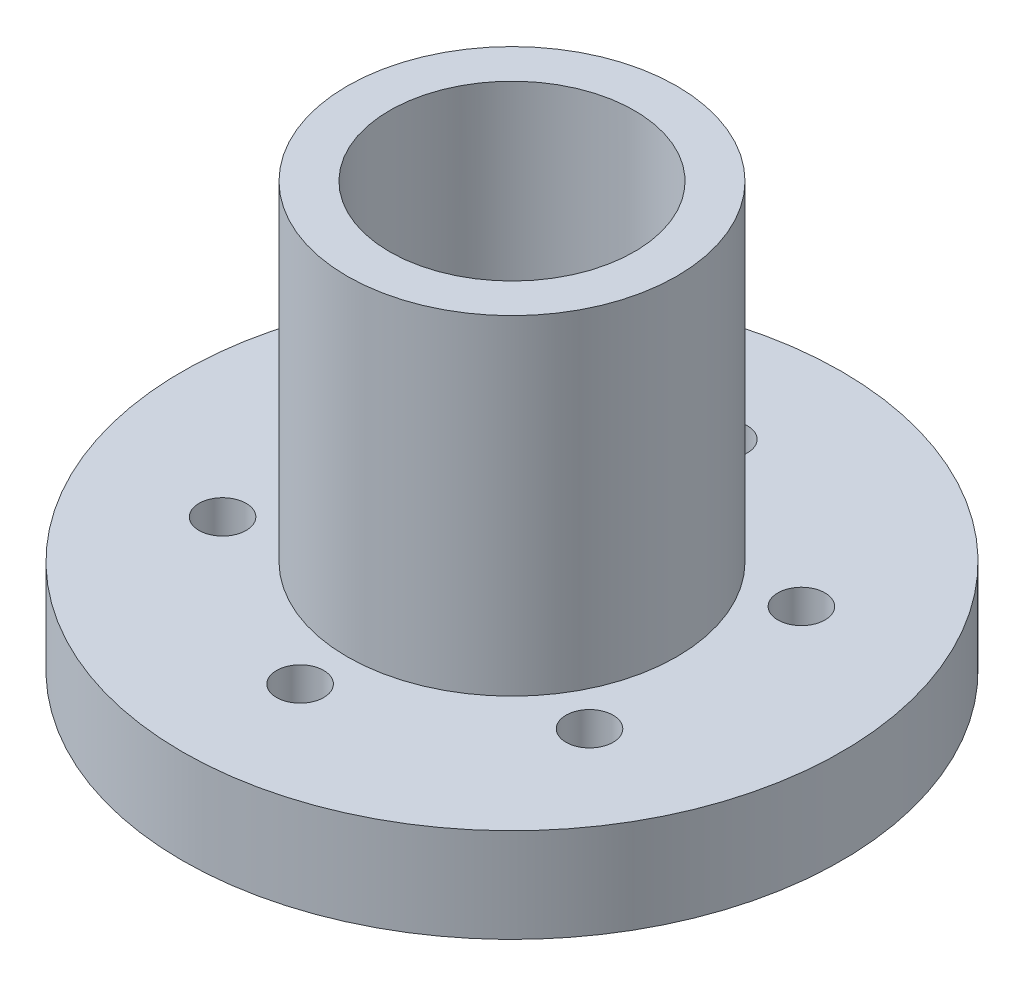
SolidWorks part; units mm, degrees
ref_plane "Front Plane" through (0, 0, 0) normal (0, 0, 1) x (1, 0, 0)
ref_plane "Top Plane" through (0, 0, 0) normal (0, 1, 0) x (1, 0, 0)
ref_plane "Right Plane" through (0, 0, 0) normal (1, 0, 0) x (0, 0, -1)
sketch "Sketch1" plane through (0, 0, 0) normal (0, 1, 0) x (1, 0, 0)
  circle A0 centre (0, 0) radius 35
  circle A1 centre (0, 0) radius 22.5 construction
  circle A2 centre (0, 0) radius 5
  circle A3 centre (0, 22.5) radius 2.5
  circle A4 centre (19.4856, 11.25) radius 2.5
  circle A5 centre (19.4856, -11.25) radius 2.5
  circle A6 centre (0, -22.5) radius 2.5
  circle A7 centre (-19.4856, -11.25) radius 2.5
  circle A8 centre (-19.4856, 11.25) radius 2.5
  point P19 (0, 0)
  dimension "D1" = 70
  dimension "D2" = 10
  dimension "D3" = 45
  dimension "D4" = 5
  dimension "D5" = 6
extrude "Boss-Extrude1" add sketch "Sketch1" along normal blind 10
sketch "Sketch2" plane through (0, 0, 0) normal (0, -1, 0) x (1, 0, 0)
  circle A0 centre (0, 0) radius 16
  dimension "D1" = 32
extrude "Cut-Extrude1" cut sketch "Sketch2" against normal blind 5
sketch "Sketch5" plane through (0, 10, 0) normal (0, 1, 0) x (1, 0, 0)
  circle A0 centre (0, 0) radius 13
  dimension "D1" = 26
extrude "Cut-Extrude2" cut sketch "Sketch5" against normal up to surface (5 mm away) up to face at (0, 5, -5)
sketch "Sketch6" plane through (0, 10, 0) normal (0, 1, 0) x (1, 0, 0)
  circle A0 centre (0, 0) radius 13
  circle A1 centre (0, 0) radius 17.5
  circle A2 centre (0, 0) radius 13 construction
  dimension "D1" = 35
extrude "Boss-Extrude2" add sketch "Sketch6" along normal blind 35
